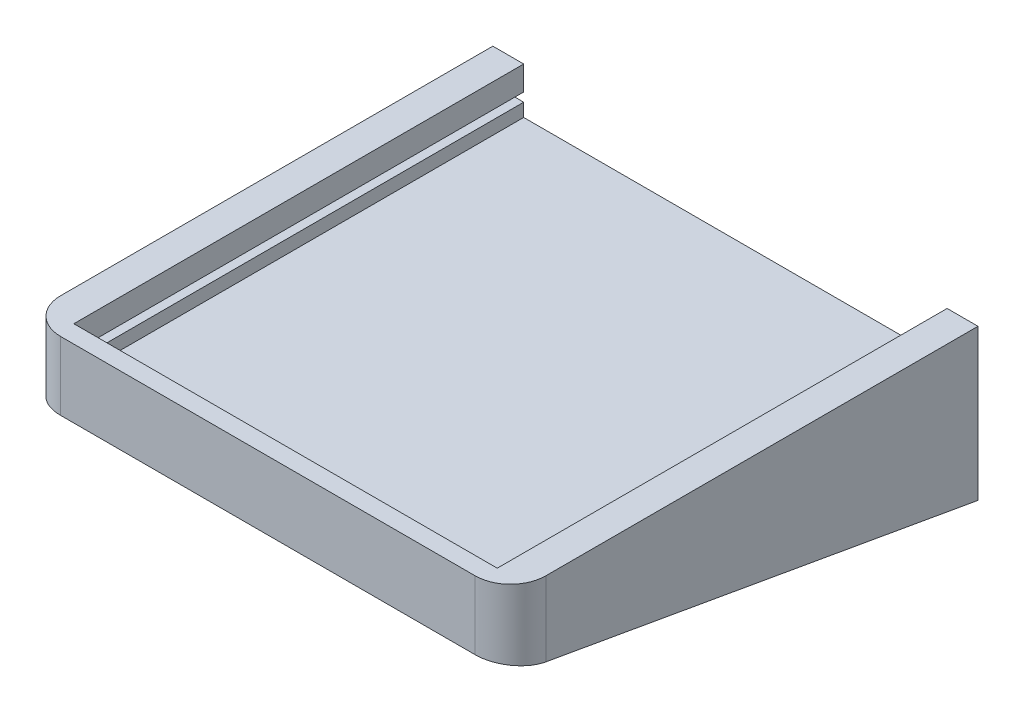
SolidWorks part; units mm, degrees
ref_plane "Plan de face" through (0, 0, 0) normal (0, 0, 1) x (1, 0, 0)
ref_plane "Plan de dessus" through (0, 0, 0) normal (0, 1, 0) x (1, 0, 0)
ref_plane "Plan de droite" through (0, 0, 0) normal (1, 0, 0) x (0, 0, -1)
sketch "Esquisse2" plane through (0, 0, 0) normal (0, 1, 0) x (1, 0, 0)
  line L1 (0, 0) -> (110, 0)
  line L2 (0, 0) -> (0, 106)
  line L3 (0, 106) -> (110, 106)
  line L4 (110, 0) -> (110, 106)
  dimension "D1" = 110
  dimension "D2" = 106
extrude "Boss.-Extru.3" add sketch "Esquisse2" along normal blind 5
sketch "Esquisse3" plane through (0, 5, 0) normal (0, 1, 0) x (1, 0, 0)
  line L0 (7, 106) -> (7, 4)
  line L1 (0, 106) -> (110, 106)
  line L2 (0, 106) -> (0, 0)
  line L3 (0, 0) -> (110, 0)
  line L4 (110, 106) -> (110, 0)
  line L5 (7, 4) -> (103, 4)
  line L6 (103, 4) -> (103, 106)
  line M8 (0, 106) -> (0, 0)
  line M9 (0, 0) -> (110, 0)
  line M10 (110, 0) -> (110, 106)
  line M11 (110, 106) -> (0, 106)
  dimension "D1" = 7
  dimension "D2" = 7
  dimension "D3" = 4
extrude "Boss.-Extru.4" add sketch "Esquisse3" along normal blind 3 contours L6 L5 L0 M11 M8 M9 M10
sketch "Esquisse4" plane through (0, 8, 0) normal (0, 1, 0) x (1, 0, 0)
  line L0 (4, 106) -> (4, 4)
  line L7 (106, 106) -> (106, 4)
  line L15 (4, 106) -> (0, 106)
  line L16 (0, 106) -> (0, 0)
  line L17 (0, 0) -> (110, 0)
  line L18 (110, 0) -> (110, 106)
  line L19 (110, 106) -> (106, 106)
  line L21 (4, 4) -> (106, 4)
  dimension "D1" = 4
  dimension "D2" = 4
  dimension "D3" = 4
extrude "Boss.-Extru.5" add sketch "Esquisse4" along normal blind 2 contours L0 L21 L7 L19 L18 L17 L16 L15
sketch "Esquisse6" plane through (0, 10, 0) normal (0, 1, 0) x (1, 0, 0)
  line L0 (103, 4) -> (103, 106) construction
  line L1 (0, 106) -> (7, 106)
  line L2 (0, 106) -> (0, 4)
  line L4 (7, 106) -> (7, 4)
  line L6 (103, 4) -> (103, 106)
  line L7 (103, 106) -> (110, 106)
  line L8 (110, 4) -> (110, 106)
  line L9 (103, 4) -> (103, 106) construction
  line L11 (110, 0) -> (0, 0)
  line L12 (110, 0) -> (110, 4)
  line L13 (103, 4) -> (7, 4)
  line L14 (0, 0) -> (0, 4)
extrude "Boss.-Extru.6" add sketch "Esquisse6" along normal blind 5.5
sketch "Esquisse8" plane through (110, 0, 0) normal (1, 0, 0) x (0, 0, -1)
  line L0 (0, 0) -> (106, 0)
  line L1 (0, 0) -> (106, 0) construction
  line L2 (106, 0) -> (106, -18.6907)
  line L3 (106, -18.6907) -> (0, 0)
  line L5 (106, 15.5) -> (106, 0) construction
  dimension "D1" = 10
extrude "Boss.-Extru.7" add sketch "Esquisse8" against normal blind 110
sketch "Esquisse7" plane through (0, 0, -106) normal (0, 0, -1) x (-1, 0, 0)
  line L0 (-103, 8) -> (-103, 5) construction
  line L1 (-103, 8) -> (-106, 8) construction
  line L2 (-7, 8) -> (-7, 5) construction
  line L3 (-7, 8) -> (-4, 8) construction
  circle A0 centre (-103, 0) radius 2.35
  circle A1 centre (-7, 0) radius 2.35
  dimension "D1" = 4.7
  dimension "D2" = 4.7
  dimension "D3" = 0
  dimension "D4" = 8
  dimension "D5" = 0
  dimension "D6" = 8
extrude "Enlèv. mat.-Extru.1" cut sketch "Esquisse7" against normal blind 12
fillet "Congé3" radius 8 2 edges at (110, 7.75, 0) (0, 7.75, 0)
sketch "Esquisse9" plane through (0, 0, 0) normal (0, -0.9848, 0.1736) x (1, 0, 0)
  line L0 (0, -8.1234) -> (0, -107.6352) construction
  line L1 (14, -8) -> (96, -8)
  line L2 (8, -14) -> (8, -97.6352)
  line L3 (14, -103.6352) -> (96, -103.6352)
  line L4 (102, -14) -> (102, -97.6352)
  line L5 (110, -8.1234) -> (110, -107.6352) construction
  line L6 (8, 0) -> (102, 0) construction
  line L7 (0, -107.6352) -> (110, -107.6352) construction
  arc A0 (8, -97.6352) -> (14, -103.6352) centre (14, -97.6352) ccw
  arc A1 (96, -103.6352) -> (102, -97.6352) centre (96, -97.6352) ccw
  arc A2 (96, -8) -> (102, -14) centre (96, -14) cw
  arc A3 (14, -8) -> (8, -14) centre (14, -14) ccw
  dimension "D5" = 6
  dimension "D1" = 8
  dimension "D2" = 8
  dimension "D3" = 8
  dimension "D4" = 4
extrude "Enlèv. mat.-Extru.2" cut sketch "Esquisse9" against normal blind 4 contours L2 A0 L3 A1 L4 A2 L1 A3
chamfer "Chanfrein1" distance 0.5 angle 45 2 edges at (100.65, 0, -106) (4.65, 0, -106)
